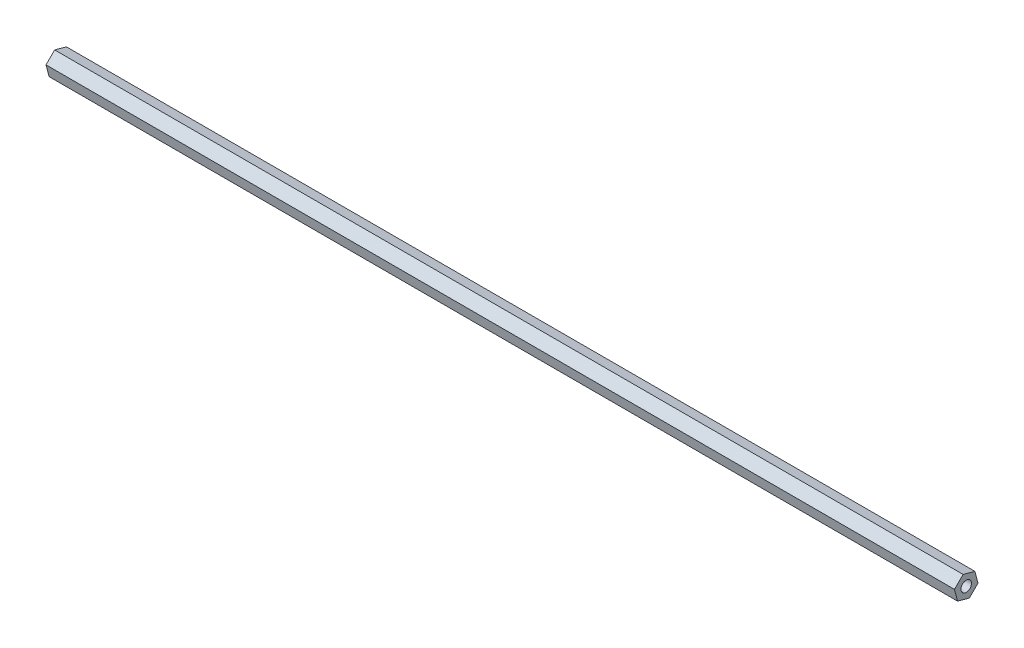
SolidWorks part; units mm, degrees
ref_plane "Front Plane" through (0, 0, 0) normal (0, 0, 1) x (1, 0, 0)
ref_plane "Top Plane" through (0, 0, 0) normal (0, 1, 0) x (1, 0, 0)
ref_plane "Right Plane" through (0, 0, 0) normal (1, 0, 0) x (0, 0, -1)
sketch "Sketch1" plane through (0, 0, 0) normal (1, 0, 0) x (0, 0, -1)
  line L1 (5.206, 5.1634) -> (-1.8687, 7.0902)
  line L2 (-1.8687, 7.0902) -> (-7.0747, 1.9268)
  line L3 (-7.0747, 1.9268) -> (-5.206, -5.1634)
  line L4 (-5.206, -5.1634) -> (1.8687, -7.0902)
  line L5 (1.8687, -7.0902) -> (7.0747, -1.9268)
  line L6 (7.0747, -1.9268) -> (5.206, 5.1634)
  dimension "D2" = 12.7
extrude "Boss-Extrude1" add sketch "Sketch1" along normal blind 546.1
sketch "Sketch2" plane through (546.1, 0, 0) normal (1, 0, 0) x (0, 0, -1)
  circle A0 centre (0, 0) radius 3.175
  dimension "D1" = 6.35
extrude "Cut-Extrude1" cut sketch "Sketch2" against normal through all
